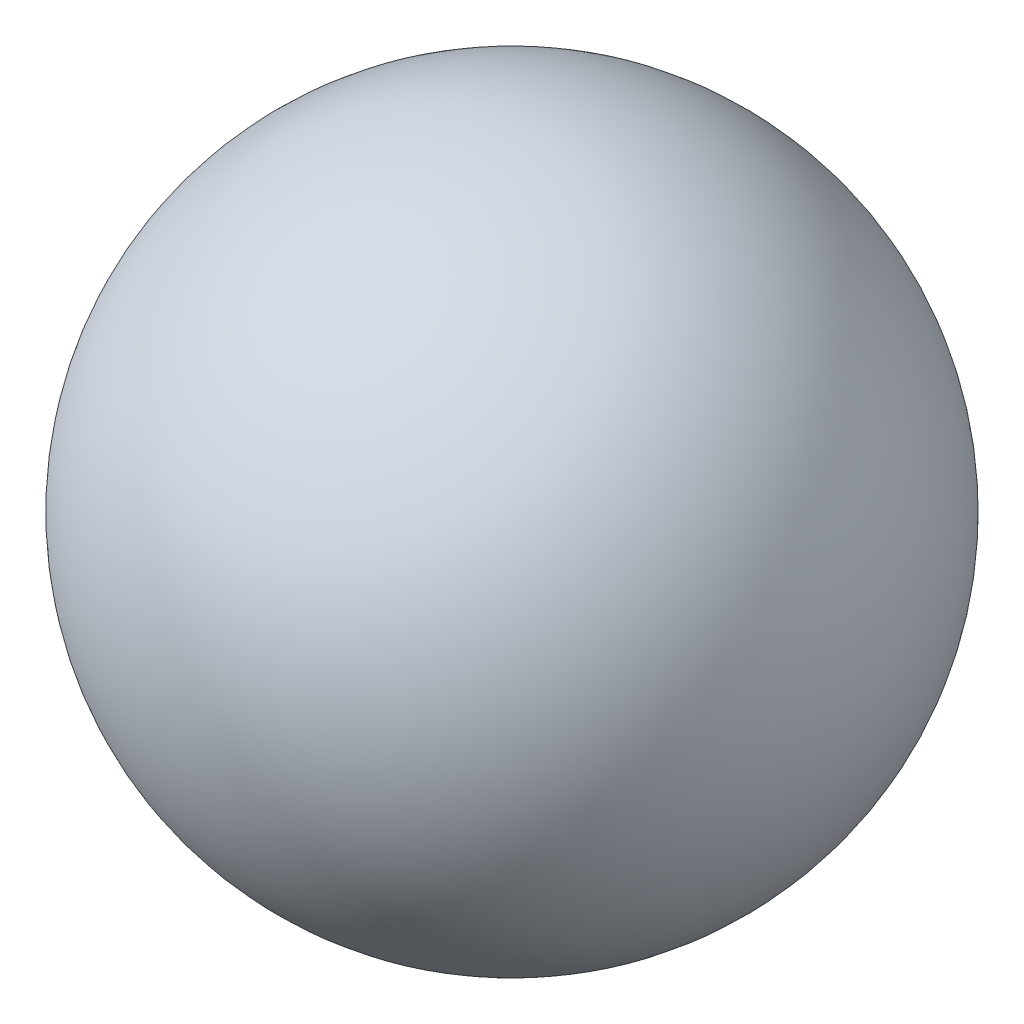
SolidWorks part; units mm, degrees
ref_plane "前视基准面" through (0, 0, 0) normal (0, 0, 1) x (1, 0, 0)
ref_plane "上视基准面" through (0, 0, 0) normal (0, 1, 0) x (1, 0, 0)
ref_plane "右视基准面" through (0, 0, 0) normal (1, 0, 0) x (0, 0, -1)
sketch "草图1" plane through (0, 0, 0) normal (0, 0, 1) x (1, 0, 0)
  line L0 (0, 0) -> (0, 21.6464) construction
  line L1 (0, 0) -> (0, -16.6941) construction
  line L2 (0, 12) -> (0, -12)
  arc A0 (0, -12) -> (0, 12) centre (0, 0) ccw
  dimension "D1" = 24
revolve "旋转1" add sketch "草图1" angle 360 about L0
